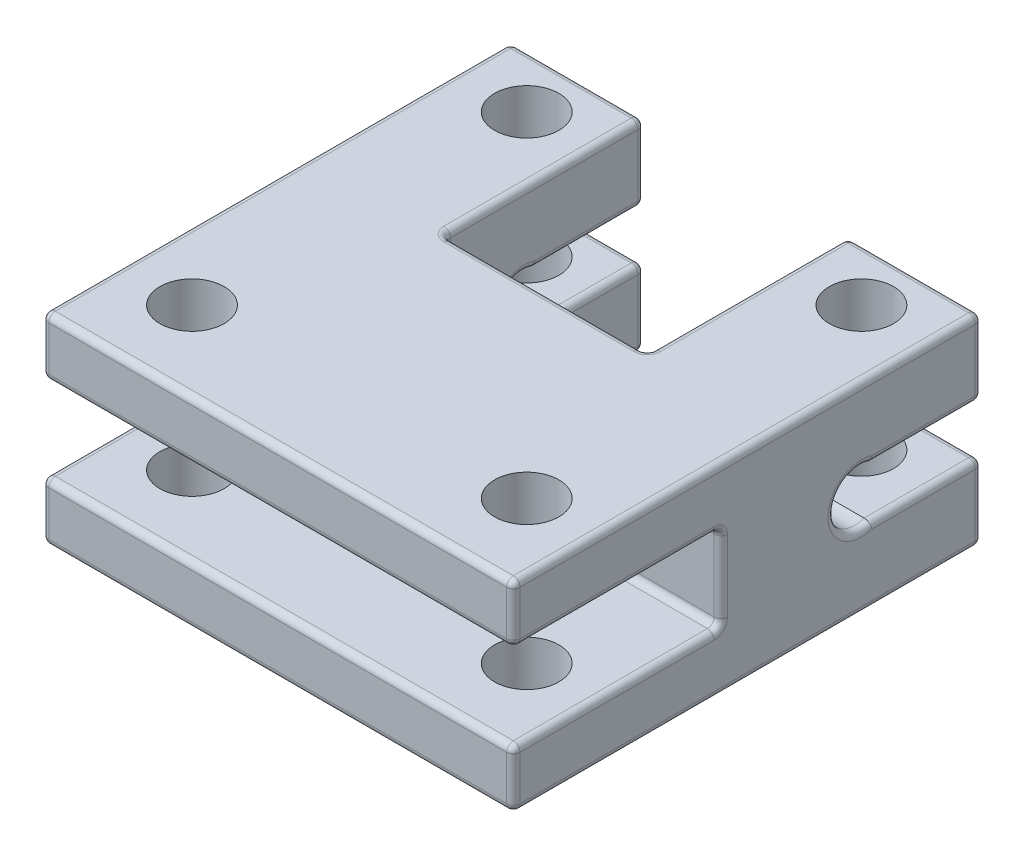
SolidWorks part; units mm, degrees
material "ABS"
ref_plane "Front" through (0, 0, 0) normal (0, 0, 1) x (1, 0, 0)
ref_plane "Top" through (0, 0, 0) normal (0, 1, 0) x (1, 0, 0)
ref_plane "Right" through (0, 0, 0) normal (1, 0, 0) x (0, 0, -1)
sketch "Esquisse2" plane through (0, 0, 0) normal (1, 0, 0) x (0, 0, -1)
  line L0 (35, 0) -> (0, 0)
  line L2 (0, -15) -> (35, -15)
  line L3 (35, -15) -> (35, -9.375)
  line L4 (35, -9.375) -> (26.696, -9.375)
  line L5 (26.696, -5.625) -> (35, -5.625)
  line L6 (35, -5.625) -> (35, 0)
  line L7 (0, -15) -> (0, -10.675)
  line L8 (0, -10.675) -> (15.5, -10.675)
  line L9 (15.5, -10.675) -> (15.5, -4.325)
  line L10 (15.5, -4.325) -> (0, -4.325)
  line L11 (0, -4.325) -> (0, 0)
  arc A0 (26.696, -9.375) -> (26.696, -5.625) centre (26, -7.5) cw
  dimension "D4" = 2
  dimension "D1" = 35
  dimension "D2" = 6.35
  dimension "D3" = 3.75
  dimension "D5" = 9
  dimension "D6" = 15
  dimension "D7" = 15.5
extrude "Boss.-Extru.1" add sketch "Esquisse2" along normal blind 10
ref_plane "Plan1" through (-7.6, 0, 0) normal (1, 0, 0) x (0, 0, -1)
sketch "Esquisse3" plane through (0, 0, 0) normal (-1, 0, 0) x (0, 0, 1)
  line L0 (0, 0) -> (0, -4.325)
  line L1 (0, -4.325) -> (-15.5, -4.325)
  line L2 (-15.5, -4.325) -> (-15.5, -10.675)
  line L3 (-15.5, -10.675) -> (0, -10.675)
  line L4 (0, -10.675) -> (0, -15)
  line L5 (0, -15) -> (-20, -15)
  line L6 (-20, -15) -> (-20, 0)
  line L7 (-20, 0) -> (0, 0)
  dimension "D1" = 20
extrude "Boss.-Extru.2" add sketch "Esquisse3" along normal blind 7.6
mirror "Symétrie5" about plane through (-7.6, 0, 0) normal (1, 0, 0) of bodies 107
hole_wizard "Dégagement M41" positions "Esquisse8" profile "Esquisse9" hole size "M4" standard "Ansi Metric" end condition through all
sketch "Esquisse8" plane through (0, 0, 0) normal (0, 1, 0) x (1, 0, 0)
  line L0 (10, 35) -> (10, 0) construction
  line L1 (10, 0) -> (-25.2, 0) construction
  line L2 (10, 35) -> (0, 35) construction
  point P0 (5, 6)
  point P2 (-20, 6)
  point P14 (5, 31)
  point P16 (-20, 31)
  dimension "D1" = 25
  dimension "D2" = 5
  dimension "D3" = 6
  dimension "D4" = 4
sketch "Esquisse9" plane through (5, 0, -6) normal (1, 0, 0) x (0, 0, 1)
  line L0 (0, 0) -> (0, 15)
  line L1 (0, 15) -> (2.4, 15)
  line L2 (2.4, 15) -> (2.4, 0)
  line L5 (2.4, 0) -> (0, 0)
  line L11 (0, -6.35) -> (0, 107.95) construction
  dimension "Diamètre du perçage jusqu'au prochain" = 4.8
  dimension "Profondeur du perçage jusqu'au prochain" = 15
fillet "Congé1" radius 0.5 56 edges at (-7.6, -4.325, 0) (-7.6, 0, 0) (-7.6, -15, 0) (-7.6, -10.675, 0) (-7.6, -10.675, -15.5) (-7.6, -4.325, -15.5) (-25.2, 0, -17.5) (-25.2, -2.1625, 0) (-25.2, -4.325, -7.75) (-25.2, -7.5, -15.5) (-25.2, -10.675, -7.75) (-25.2, -12.8375, 0) (-25.2, -15, -17.5) (-25.2, -9.375, -30.848) (-25.2, -7.5, -24) (-25.2, -5.625, -30.848) (10, -5.625, -30.848) (10, -7.5, -24) (10, -9.375, -30.848) (10, -15, -17.5) (10, -12.8375, 0) (10, -10.675, -7.75) (10, -7.5, -15.5) (10, -4.325, -7.75) (10, -2.1625, 0) (10, 0, -17.5) (5, -5.625, -35) (10, -2.8125, -35) (5, 0, -35) (5, -15, -35) (10, -12.1875, -35) (5, -9.375, -35) (-20.2, -9.375, -35) (-25.2, -12.1875, -35) (-20.2, -15, -35) (-20.2, 0, -35) (-25.2, -2.8125, -35) (-20.2, -5.625, -35) (-15.2, 0, -27.5) (-15.2, -2.8125, -35) (-15.2, -5.625, -30.848) (-15.2, -7.5, -24) (-15.2, -9.375, -30.848) (-15.2, -12.1875, -35) (-15.2, -15, -27.5) (0, -15, -27.5) (0, -12.1875, -35) (0, -9.375, -30.848) (0, -7.5, -24) (0, -5.625, -30.848) (0, -2.8125, -35) (0, 0, -27.5) (-7.6, 0, -20) (-15.2, -7.5, -20) (-7.6, -15, -20) (0, -7.5, -20)
